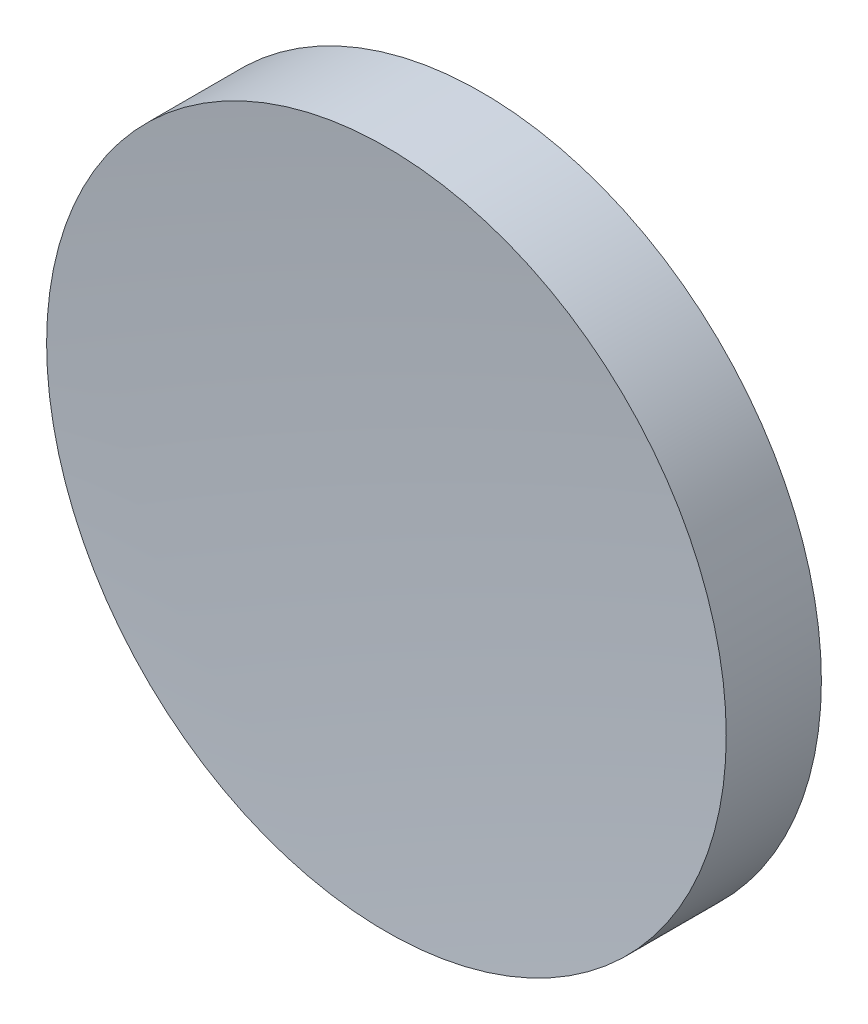
SolidWorks part; units mm, degrees
material "Verre"
ref_plane "Plan de face" through (0, 0, 0) normal (0, 0, 1) x (1, 0, 0)
ref_plane "Plan de dessus" through (0, 0, 0) normal (0, 1, 0) x (1, 0, 0)
ref_plane "Plan de droite" through (0, 0, 0) normal (1, 0, 0) x (0, 0, -1)
sketch "Esquisse1" plane through (0, 0, 0) normal (0, 0, 1) x (1, 0, 0)
  circle A0 centre (0, 0) radius 125
  dimension "D1" = 250
extrude "Boss.-Extru.1" add sketch "Esquisse1" along normal blind 35
sketch "Esquisse2" plane through (0, 0, 0) normal (0, 1, 0) x (1, 0, 0)
  line L0 (0, 0) -> (0, -835) construction
  line L1 (-125, -35) -> (125, -35) construction
  line L2 (0, -1630.1097) -> (0, -30.1097)
  line L3 (0, -1630.1097) -> (1600, -1630.1097)
  arc A0 (1600, -1630.1097) -> (0, -30.1097) centre (0, -1630.1097) ccw
  dimension "D1" = 3200
  dimension "D2" = 800
revolve "Enlèvement de matière-Révolution6" cut sketch "Esquisse2" angle 360 about L0
